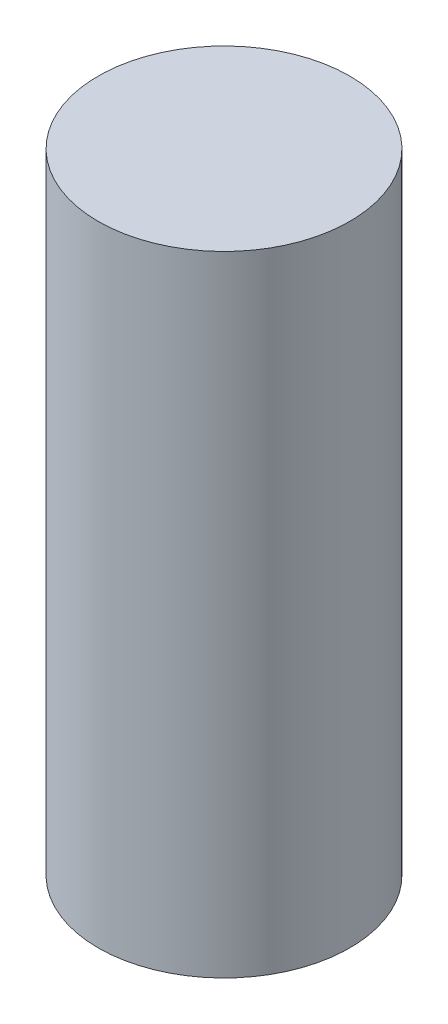
SolidWorks part; units mm, degrees
ref_plane "Front Plane" through (0, 0, 0) normal (0, 0, 1) x (1, 0, 0)
ref_plane "Top Plane" through (0, 0, 0) normal (0, 1, 0) x (1, 0, 0)
ref_plane "Right Plane" through (0, 0, 0) normal (1, 0, 0) x (0, 0, -1)
sketch "Sketch1" plane through (0, 0, 0) normal (0, 1, 0) x (1, 0, 0)
  circle A0 centre (0, 0) radius 10.16
  dimension "D1" = 20.32
extrude "Boss-Extrude1" add sketch "Sketch1" along normal blind 50.8
